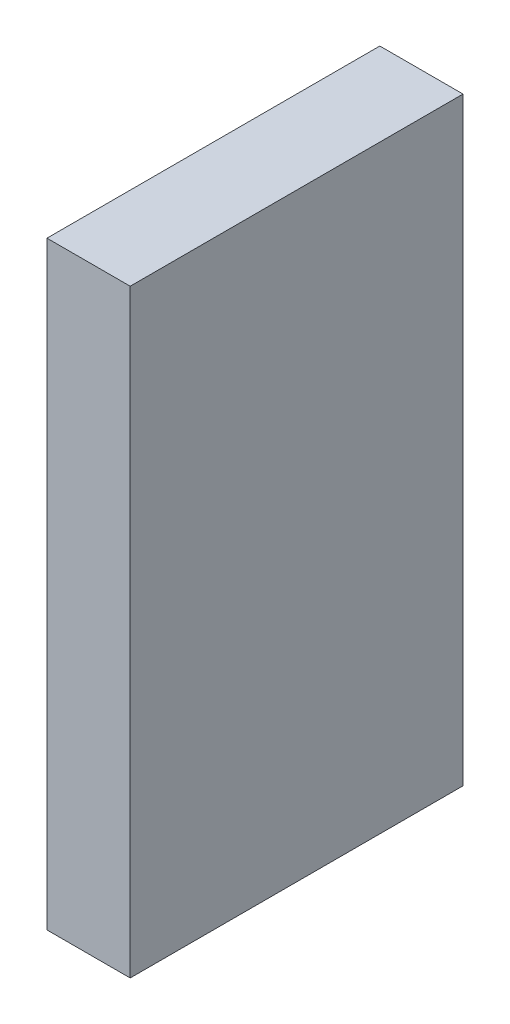
SolidWorks part; units mm, degrees
ref_plane "Front Plane" through (0, 0, 0) normal (0, 0, 1) x (1, 0, 0)
ref_plane "Top Plane" through (0, 0, 0) normal (0, 1, 0) x (1, 0, 0)
ref_plane "Right Plane" through (0, 0, 0) normal (1, 0, 0) x (0, 0, -1)
sketch "Sketch1" plane through (0, 0, 0) normal (0, 1, 0) x (1, 0, 0)
  line L1 (-1.25, 5) -> (1.25, 5)
  line L2 (-1.25, 5) -> (-1.25, -5)
  line L3 (-1.25, -5) -> (1.25, -5)
  line L4 (1.25, 5) -> (1.25, -5)
  line L5 (-1.25, 5) -> (1.25, -5) construction
  line L6 (-1.25, -5) -> (1.25, 5) construction
  point P0 (0, 0)
  dimension "D1" = 10
  dimension "D2" = 2.5
extrude "Boss-Extrude1" add sketch "Sketch1" along normal blind 18
